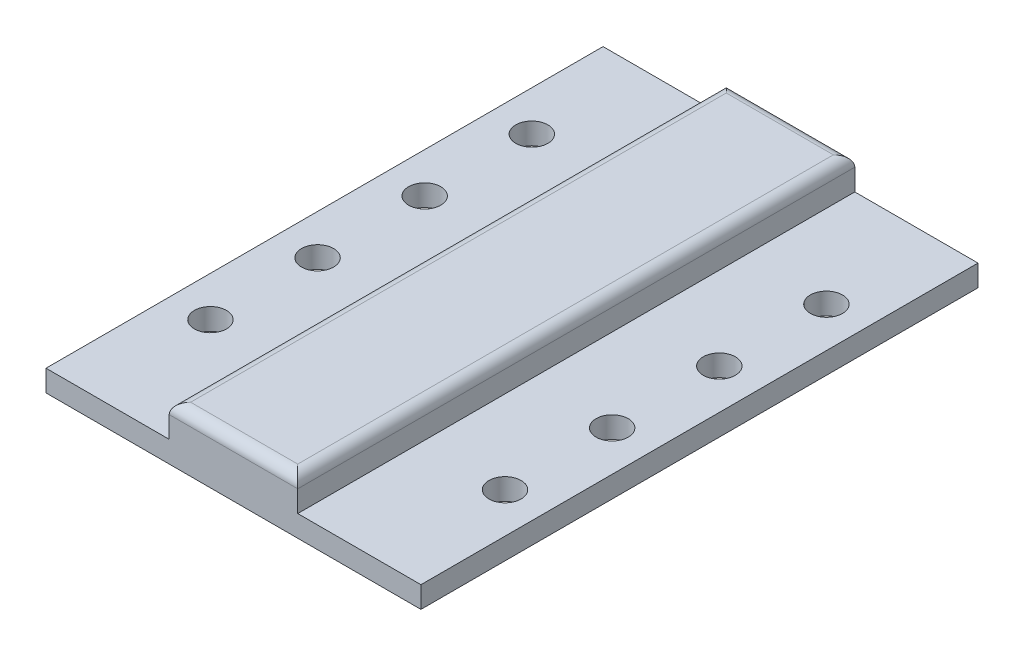
SolidWorks part; units mm, degrees
ref_plane "Спереди" through (0, 0, 0) normal (0, 0, 1) x (1, 0, 0)
ref_plane "Сверху" through (0, 0, 0) normal (0, 1, 0) x (1, 0, 0)
ref_plane "Справа" through (0, 0, 0) normal (1, 0, 0) x (0, 0, -1)
sketch "Эскиз1" plane through (0, 0, 0) normal (0, 1, 0) x (1, 0, 0)
  line L0 (17.5, -26) -> (-17.5, -26)
  line L1 (17.5, -26) -> (17.5, 26)
  line L2 (17.5, 26) -> (-17.5, 26)
  line L3 (-17.5, -26) -> (-17.5, 26)
extrude "Бобышка-Вытянуть1" add sketch "Эскиз1" along normal blind 2
sketch "Эскиз2" plane through (0, 0, 0) normal (0, 0, 1) x (1, 0, 0)
  line L0 (-17.5, 2) -> (17.5, 2) construction
  line L1 (-6, 2) -> (6, 2)
  line L2 (-6, 2) -> (-6, 5)
  line L3 (-6, 5) -> (6, 5)
  line L4 (6, 2) -> (6, 5)
  line L7 (0, 5) -> (0, 2) construction
  line L8 (0, 0) -> (0, 2) construction
  line L9 (-17.5, 0) -> (17.5, 0) construction
  dimension "D1" = 0
  dimension "D2" = 12
  dimension "D3" = 3
extrude "Бобышка-Вытянуть2" add sketch "Эскиз2" along normal up to surface and the other way up to surface up to face at (0, 1, 26) other way up to face at (0, 1, -26)
sketch "Эскиз3" plane through (0, 2, 0) normal (0, 1, 0) x (1, 0, 0)
  line L0 (0, 26) -> (0, -26) construction
  line L5 (-6, 26) -> (6, 26) construction
  line L6 (-6, -26) -> (6, -26) construction
  circle A0 centre (13.75, 15.6) radius 1.5
  circle A1 centre (-13.75, 15.6) radius 1.5
  circle A2 centre (-13.75, 5.6) radius 1.5
  circle A3 centre (13.75, 5.6) radius 1.5
  circle A4 centre (-13.75, -4.4) radius 1.5
  circle A5 centre (13.75, -4.4) radius 1.5
  circle A6 centre (-13.75, -14.4) radius 1.5
  circle A7 centre (13.75, -14.4) radius 1.5
  dimension "D1" = 4
extrude "Вырез-Вытянуть1" cut sketch "Эскиз3" against normal blind 10
fillet "Скругление1" radius 1 4 edges at (0, 5, 26) (0, 5, -26) (-6, 5, 0) (6, 5, 0)
sketch "Эскиз4" plane through (0, 2, 0) normal (0, 1, 0) x (1, 0, 0)
  line L0 (-17.5, 0) -> (17.5, 0) construction
  line L1 (-17.5, 26) -> (-17.5, -26) construction
  line L2 (17.5, -26) -> (17.5, 26) construction
  line L3 (-13.75, 15.6) -> (13.75, 15.6) construction
  line L4 (13.75, 15.6) -> (13.75, 5.6) construction
  line L5 (13.75, 5.6) -> (-13.75, 5.6) construction
  line L6 (-13.75, 5.6) -> (-13.75, -4.4) construction
  line L7 (-13.75, -4.4) -> (13.75, -4.4) construction
  line L8 (13.75, -4.4) -> (13.75, -14.4) construction
  line L9 (13.75, -14.4) -> (-13.75, -14.4) construction
  line L10 (-6, 26) -> (-17.5, 26) construction
  line L12 (-17.5, -26) -> (-6, -26) construction
  dimension "D1" = 10.4
  dimension "D2" = 11.6
